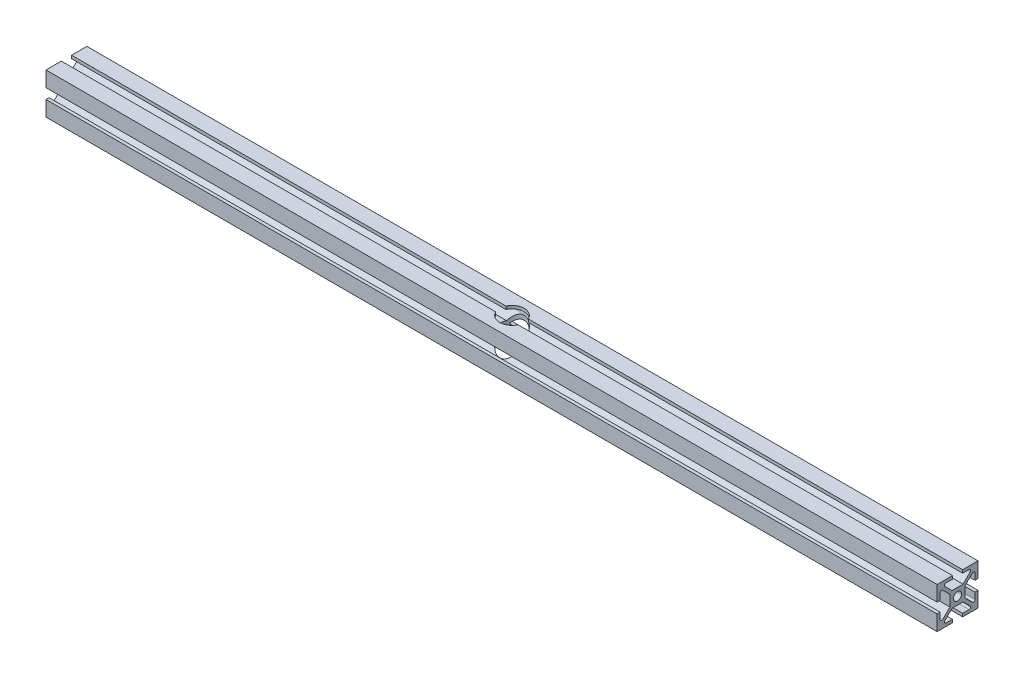
SolidWorks part; units mm, degrees
ref_plane "Plan de face" through (0, 0, 0) normal (0, 0, 1) x (1, 0, 0)
ref_plane "Plan de dessus" through (0, 0, 0) normal (0, 1, 0) x (1, 0, 0)
ref_plane "Plan de droite" through (0, 0, 0) normal (1, 0, 0) x (0, 0, -1)
sketch "Esquisse1" plane through (0, 0, 0) normal (1, 0, 0) x (0, 0, -1)
  line L0 (0, 0) -> (0, -14.4844) construction
  line L1 (-10, 10) -> (-2.5, 10)
  line L2 (-10, 10) -> (-10, 2.5)
  line L3 (-10, -10) -> (-2.5, -10)
  line L4 (10, 10) -> (10, 2.5)
  line L5 (-10, 10) -> (10, -10) construction
  line L6 (-10, -10) -> (10, 10) construction
  line L7 (-2.6893, 3.75) -> (2.6893, 3.75)
  line L8 (-3.75, 2.6893) -> (-3.75, -2.6893)
  line L9 (-2.6893, -3.75) -> (2.6893, -3.75)
  line L10 (3.75, 2.6893) -> (3.75, -2.6893)
  line L11 (-3.75, 3.75) -> (3.75, -3.75) construction
  line L12 (-3.75, -3.75) -> (3.75, 3.75) construction
  line L13 (-2.5, 8.5) -> (-2.5, 10)
  line L14 (2.5, 8.5) -> (2.5, 10)
  line L15 (8.5, 2.5) -> (10, 2.5)
  line L16 (8.5, -2.5) -> (10, -2.5)
  line L17 (-2.6893, 3.75) -> (-3.75, 3.75) construction
  line L18 (-7.4393, -8.5) -> (-2.6893, -3.75)
  line L19 (2.5, 8.5) -> (7.4393, 8.5)
  line L20 (7.4393, 8.5) -> (2.6893, 3.75)
  line L21 (-2.5, -8.5) -> (-7.4393, -8.5)
  line L22 (-2.5, 8.5) -> (-7.4393, 8.5)
  line L23 (-7.4393, 8.5) -> (-2.6893, 3.75)
  line L24 (8.5, 2.5) -> (8.5, 7.4393)
  line L25 (8.5, 7.4393) -> (3.75, 2.6893)
  line L26 (8.5, -7.4393) -> (3.75, -2.6893)
  line L27 (8.5, -2.5) -> (8.5, -7.4393)
  line L28 (8.5, -2.5) -> (10, -2.5)
  line L29 (0, 0) -> (19.7872, 0) construction
  line L30 (7.4393, -8.5) -> (2.6893, -3.75)
  line L31 (2.5, -8.5) -> (7.4393, -8.5)
  line L32 (2.5, -8.5) -> (2.5, -10)
  line L33 (-2.5, -8.5) -> (-2.5, -10)
  line L34 (-2.6893, -3.75) -> (2.6893, -3.75)
  line L35 (-8.5, -2.5) -> (-10, -2.5)
  line L36 (-8.5, -2.5) -> (-8.5, -7.4393)
  line L37 (-8.5, -7.4393) -> (-3.75, -2.6893)
  line L38 (-8.5, 7.4393) -> (-3.75, 2.6893)
  line L39 (-8.5, 2.5) -> (-8.5, 7.4393)
  line L40 (-8.5, -2.5) -> (-10, -2.5)
  line L41 (-8.5, 2.5) -> (-10, 2.5)
  line L42 (-3.75, 2.6893) -> (-3.75, -2.6893)
  line L43 (-10, -2.5) -> (-10, -10)
  line L44 (2.5, -10) -> (10, -10)
  line L45 (10, -2.5) -> (10, -10)
  line L46 (2.5, 10) -> (10, 10)
  circle A0 centre (0, 0) radius 2
  point P0 (0, 0)
  point P6 (0, 0)
  dimension "D10" = 4
  dimension "D1" = 20
  dimension "D2" = 1.5
  dimension "D3" = 5
  dimension "D4" = 7.5
  dimension "D5" = 1.5
  dimension "D6" = 1.5
  dimension "D7" = 0.75
  dimension "D8" = 5
  dimension "D9" = 20
extrude "Boss.-Extru.1" add sketch "Esquisse1" along normal mid plane 436 contours L46 L14 L19 L20 L7 L23 L22 L13 L1 L2 L41 L39 L38 L8 L37 L36 L35 L43 L3 L33 L21 L18 L9 L30 L31 L32 L44 L45 L16 L27 L26 L10 L25 L24 L15 L4 A0
fillet "Congé1" radius 0.75 8 edges at (0, -7.4393, 8.5) (0, -8.5, 7.4393) (0, -8.5, -7.4393) (0, -7.4393, -8.5) (0, 7.4393, -8.5) (0, 8.5, -7.4393) (0, 7.4393, 8.5) (0, 8.5, 7.4393)
hole_wizard "Diamètre du perçage Ø12.0 (12)2" positions "Esquisse5" profile "Esquisse4" hole size "Ø12.0" standard "Ansi Metric" end condition through all
sketch "Esquisse5" plane through (0, 10, 0) normal (0, 1, 0) x (1, 0, 0)
  point P0 (0, 0)
sketch "Esquisse4" plane through (0, 10, 0) normal (1, 0, 0) x (0, 0, 1)
  line L0 (0, 0) -> (0, 20)
  line L1 (0, 20) -> (6, 20)
  line L2 (6, 20) -> (6, 0)
  line L5 (6, 0) -> (0, 0)
  line L11 (0, -6.35) -> (0, 107.95) construction
  dimension "Diamètre du perçage jusqu'au prochain" = 12
  dimension "Profondeur du perçage jusqu'au prochain" = 20
equation "\"rayon_pignon\" = 26.0313"
equation "\"largeur_robot\" = 436mm"
equation "\"largeur_chenille\"= \"RD1@Annotations\""
equation "\"espace_sous_robot\"= \"largeur_robot\" - \"largeur_chenille\" - \"largeur_chenille\""
